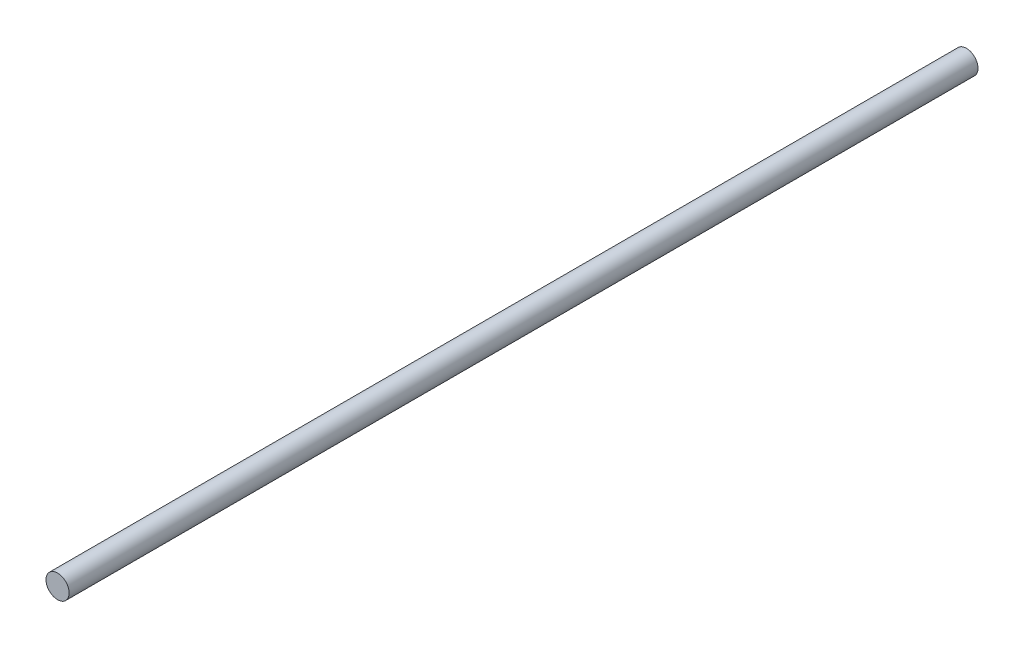
SolidWorks part; units mm, degrees
ref_plane "Front Plane" through (0, 0, 0) normal (0, 0, 1) x (1, 0, 0)
ref_plane "Top Plane" through (0, 0, 0) normal (0, 1, 0) x (1, 0, 0)
ref_plane "Right Plane" through (0, 0, 0) normal (1, 0, 0) x (0, 0, -1)
sketch "Sketch1" plane through (0, 0, 0) normal (0, 0, 1) x (1, 0, 0)
  circle A0 centre (0, 0) radius 4
  dimension "D1" = 8
extrude "Boss-Extrude1" add sketch "Sketch1" along normal blind 314
